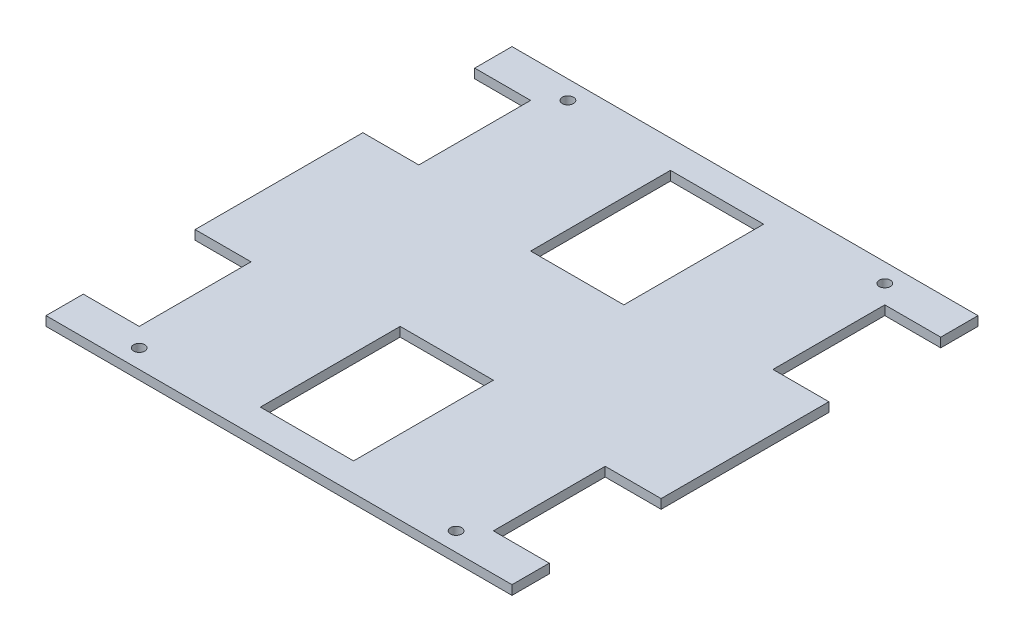
SolidWorks part; units mm, degrees
ref_plane "前视基准面" through (0, 0, 0) normal (0, 0, 1) x (1, 0, 0)
ref_plane "上视基准面" through (0, 0, 0) normal (0, 1, 0) x (1, 0, 0)
ref_plane "右视基准面" through (0, 0, 0) normal (1, 0, 0) x (0, 0, -1)
sketch "Sketch2" plane through (0, 0, 0) normal (0, 1, 0) x (1, 0, 0)
  line L0 (-125, 105) -> (-95, 105)
  line L1 (-125, -125) -> (125, -125)
  line L2 (-125, -125) -> (-125, 125)
  line L3 (-125, 125) -> (125, 125)
  line L4 (125, -125) -> (125, 125)
  line L5 (-125, -125) -> (125, 125) construction
  line L6 (-125, 125) -> (125, -125) construction
  line L7 (-95, 105) -> (-95, 45)
  line L8 (-95, 45) -> (-125, 45)
  line L9 (-125, 45) -> (-125, 105)
  line L10 (-157.2847, 0) -> (128.6703, 0)
  line L11 (0, 131.6949) -> (0, -151.8493)
  line L12 (95, 45) -> (125, 45)
  line L13 (95, 105) -> (95, 45)
  line L14 (125, 105) -> (95, 105)
  line L15 (125, 45) -> (125, 105)
  line L16 (95, -105) -> (95, -45)
  line L17 (125, -105) -> (95, -105)
  line L18 (125, -45) -> (125, -105)
  line L19 (95, -45) -> (125, -45)
  line L20 (-95, -45) -> (-125, -45)
  line L21 (-95, -105) -> (-95, -45)
  line L22 (-125, -105) -> (-95, -105)
  line L23 (-125, -45) -> (-125, -105)
  line L24 (125, -105) -> (125, -45)
  line L25 (-25, -110) -> (25, -110)
  line L26 (-25, 35) -> (25, 35)
  line L27 (-25, 35) -> (-25, 110)
  line L28 (-25, 110) -> (25, 110)
  line L29 (25, 35) -> (25, 110)
  line L30 (-25, 35) -> (25, 110) construction
  line L31 (-25, 110) -> (25, 35) construction
  line L32 (25, -35) -> (25, -110)
  line L33 (-25, -35) -> (25, -35)
  line L34 (-25, -35) -> (-25, -110)
  line L35 (-25, -110) -> (25, -35) construction
  line L36 (-25, -35) -> (25, -110) construction
  circle A0 centre (-85, 115) radius 3
  circle A1 centre (85, 115) radius 3
  circle A2 centre (85, -115) radius 3
  circle A3 centre (-85, -115) radius 3
  point P0 (0, 0)
  point P26 (0, 72.5)
  point P35 (0, -72.5)
  point P40 (0, 0)
  dimension "D5" = 6
  dimension "D1" = 250
  dimension "D2" = 30
  dimension "D3" = 60
  dimension "D4" = 20
  dimension "D6" = 10
  dimension "D7" = 40
  dimension "D8" = 15
  dimension "D9" = 50
  dimension "D10" = 35
extrude "Boss-Extrude1" add sketch "Sketch2" along normal blind 5 contours L11 L3 L2 L0 L7 L8 L10 | L22 L2 L1 L11 L10 L20 L21 | L16 L19 L4 L10 L11 L1 L17 | L14 L4 L3 L11 L10 L12 L13
